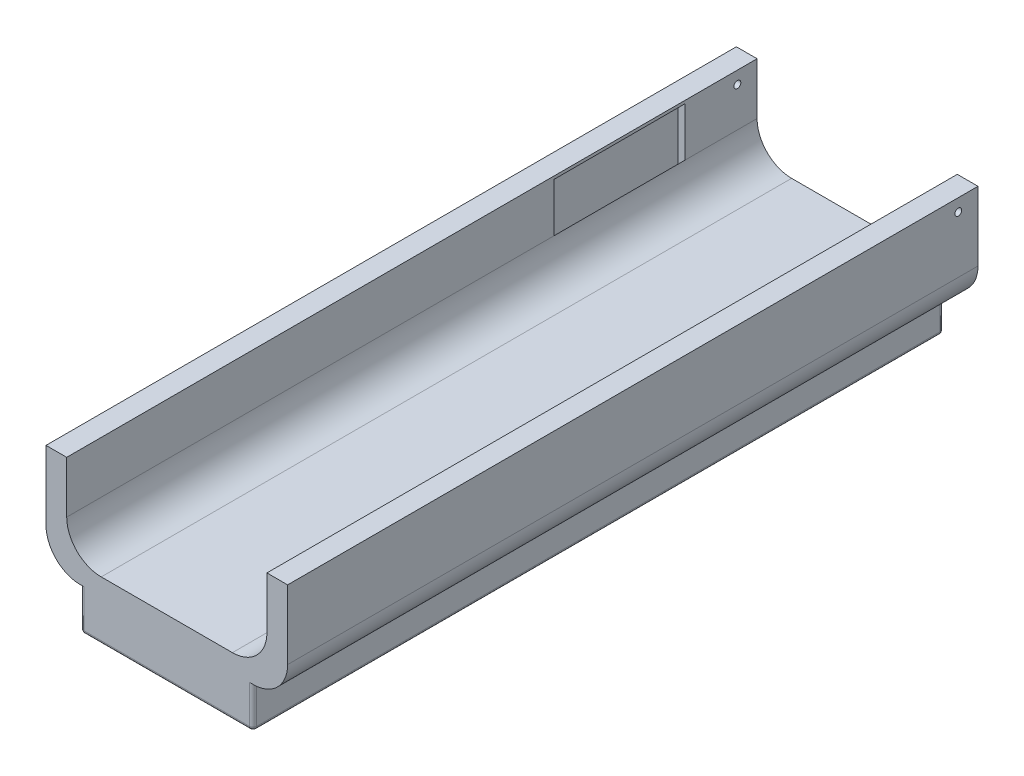
SolidWorks part; units mm, degrees
material "PETG"
ref_plane "Front Plane" through (0, 0, 0) normal (0, 0, 1) x (1, 0, 0)
ref_plane "Top Plane" through (0, 0, 0) normal (0, 1, 0) x (1, 0, 0)
ref_plane "Right Plane" through (0, 0, 0) normal (1, 0, 0) x (0, 0, -1)
sketch "Sketch1" plane through (0, 0, 0) normal (0, 0, 1) x (1, 0, 0)
  line L0 (-30.2752, -0.9088) -> (-30.2752, -25.9131)
  line L1 (-30.2752, -25.9131) -> (27.7248, -25.9131)
  line L2 (27.7248, -25.9131) -> (27.7248, -0.9088)
  line L3 (-30.2752, -0.9088) -> (-36.2752, -0.9088)
  line L4 (-36.2752, -0.9088) -> (-36.2752, -30.9088)
  line L5 (-36.2752, -30.9088) -> (33.7248, -30.9088)
  line L6 (33.7248, -30.9088) -> (33.7248, -0.9088)
  line L7 (33.7248, -0.9088) -> (27.7248, -0.9088)
  line L8 (-1.2752, -30.9088) -> (-1.2752, -27.6106) construction
  dimension "D1" = 4.9957
  dimension "D2" = 35
  dimension "D3" = 30
  dimension "D4" = 6
  dimension "D5" = 6
  dimension "D6" = 30
extrude "Boss-Extrude1" add sketch "Sketch1" along normal blind 200
fillet "Fillet1" radius 10 4 edges at (-36.2752, -30.9088, 100) (33.7248, -30.9088, 100) (-30.2752, -25.9131, 100) (27.7248, -25.9131, 100)
ref_plane "Plane1" through (30.7248, 0, 0) normal (-1, 0, 0) x (0, 0, 1)
sketch "Sketch12" plane through (-30.2752, 0, 0) normal (1, 0, 0) x (0, 0, -1)
  line L0 (-200, -0.9088) -> (0, -0.9088) construction
  line L1 (-20.87, -19.5588) -> (-58.87, -19.5588)
  line L2 (-20.87, -19.5588) -> (-20.87, -1.7588)
  line L3 (-20.87, -1.7588) -> (-58.87, -1.7588)
  line L4 (-58.87, -19.5588) -> (-58.87, -1.7588)
  line L5 (-20.87, -19.5588) -> (-58.87, -1.7588) construction
  line L6 (-20.87, -1.7588) -> (-58.87, -19.5588) construction
  line L7 (0, -15.9131) -> (0, -0.9088) construction
  point P0 (-39.87, -10.6588)
  dimension "D1" = 0.85
  dimension "D2" = 20.87
  dimension "D3" = 38
  dimension "D4" = 17.8
extrude "Cut-Extrude9" cut sketch "Sketch12" against normal blind 2
sketch "Sketch15" plane through (0, 0, 0) normal (0, 0, 1) x (1, 0, 0)
  line L0 (-26.2752, -30.9088) -> (-26.2752, -42.9088)
  line L1 (23.7248, -30.9088) -> (23.7248, -42.9088)
  line L2 (-26.2752, -42.9088) -> (23.7248, -42.9088)
  line L3 (-26.2752, -30.9088) -> (-23.2752, -30.9088)
  line L4 (-26.2752, -30.9088) -> (23.7248, -30.9088) construction
  line L8 (20.7248, -30.9088) -> (23.7248, -30.9088)
  line L9 (-23.2752, -30.9088) -> (20.7248, -30.9088)
  dimension "D2" = 12
  dimension "D3" = 3
  dimension "D4" = 3
extrude "Boss-Extrude2" add sketch "Sketch15" along normal up to surface (200 mm away) up to face at (-1.2752, -16.6006, 200)
fillet "Fillet4" radius 1 8 edges at (23.7248, -36.9088, 200) (23.7248, -36.9088, 0) (-26.2752, -36.9088, 200) (-26.2752, -36.9088, 0) (-1.2752, -42.9088, 200) (-1.2752, -42.9088, 0) (-26.2752, -42.9088, 100) (23.7248, -42.9088, 100)
sketch "Sketch17" plane through (0, 0, 0) normal (0, 0, -1) x (-1, 0, 0)
  line L0 (-20.8197, -31.6924) -> (-20.8197, -40.4239)
  line L1 (-20.8197, -40.4239) -> (23.4198, -40.4239)
  line L2 (23.4198, -40.4239) -> (23.4198, -31.6924)
  line L3 (23.4198, -31.6924) -> (-20.8197, -31.6924)
extrude "Cut-Extrude11" cut sketch "Sketch17" against normal blind 193
sketch "Sketch20" plane through (27.7248, 0, 0) normal (-1, 0, 0) x (0, 0, 1)
  circle A1 centre (5.7121, -4.5283) radius 1
  circle A2 centre (5.7121, -4.5283) radius 1
  dimension "D1" = 0
extrude "Cut-Extrude12" cut sketch "Sketch20" against normal through all both and the other way through all
